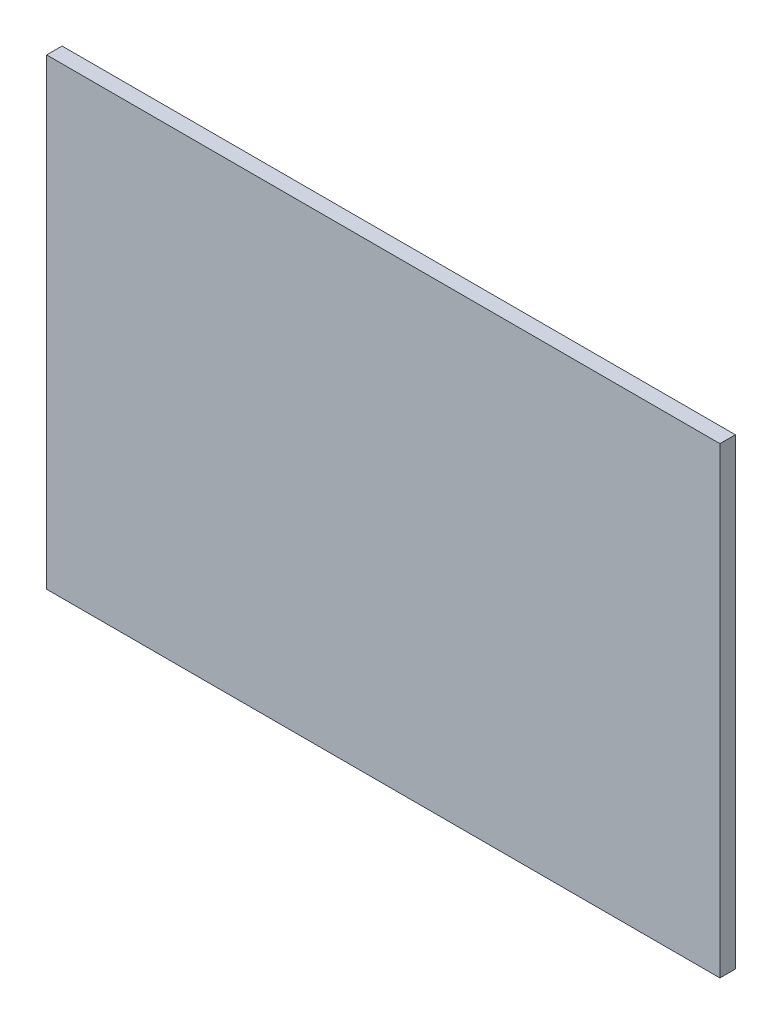
SolidWorks part; units mm, degrees
ref_plane "Front Plane" through (0, 0, 0) normal (0, 0, 1) x (1, 0, 0)
ref_plane "Top Plane" through (0, 0, 0) normal (0, 1, 0) x (1, 0, 0)
ref_plane "Right Plane" through (0, 0, 0) normal (1, 0, 0) x (0, 0, -1)
sketch "Sketch1" plane through (0, 0, 0) normal (0, 0, 1) x (1, 0, 0)
  line L2 (-52.5537, 24.2138) -> (34.7463, 24.2138)
  line L3 (-52.5537, 24.2138) -> (-52.5537, -35.7862)
  line L4 (-52.5537, -35.7862) -> (34.7463, -35.7862)
  line L5 (34.7463, 24.2138) -> (34.7463, -35.7862)
  dimension "D1" = 87.3
  dimension "D2" = 60
extrude "Boss-Extrude1" add sketch "Sketch1" along normal blind 2
